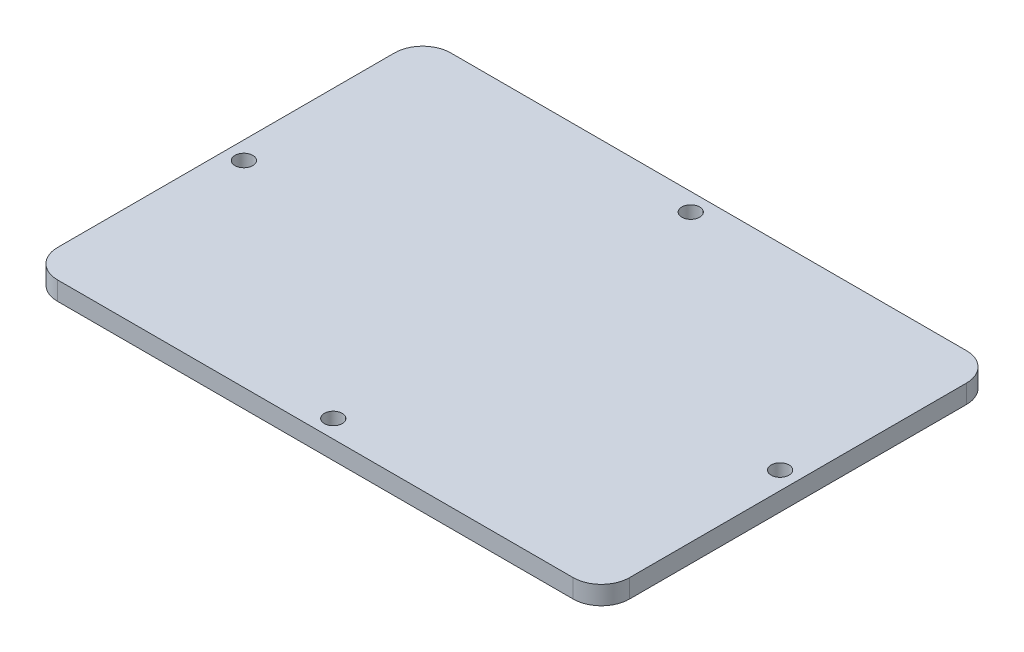
SolidWorks part; units mm, degrees
ref_plane "Front Plane" through (0, 0, 0) normal (0, 0, 1) x (1, 0, 0)
ref_plane "Top Plane" through (0, 0, 0) normal (0, 1, 0) x (1, 0, 0)
ref_plane "Right Plane" through (0, 0, 0) normal (1, 0, 0) x (0, 0, -1)
sketch "Sketch1" plane through (0, 0, 0) normal (0, 1, 0) x (1, 0, 0)
  line L1 (-50.8, -34.925) -> (50.8, -34.925)
  line L2 (-50.8, -34.925) -> (-50.8, 34.925)
  line L3 (-50.8, 34.925) -> (50.8, 34.925)
  line L4 (50.8, -34.925) -> (50.8, 34.925)
  line L5 (-50.8, -34.925) -> (50.8, 34.925) construction
  line L6 (-50.8, 34.925) -> (50.8, -34.925) construction
  point P0 (0, 0)
  point P6 (0, 0)
  point P7 (0, 0)
  dimension "D1" = 101.6
  dimension "D2" = 69.85
extrude "Boss-Extrude1" add sketch "Sketch1" along normal blind 3.302
sketch "Sketch4" plane through (0, 0, 0) normal (0, -1, 0) x (-1, 0, 0)
  circle A0 centre (0, 31.75) radius 1.5875
  circle A1 centre (-47.625, 0) radius 1.5875
  circle A2 centre (0, -31.75) radius 1.5875
  circle A3 centre (47.625, 0) radius 1.5875
  circle A8 centre (-47.625, 0) radius 1.5875 construction
  circle A9 centre (0, 31.75) radius 1.5875 construction
  circle A10 centre (0, -31.75) radius 1.5875 construction
  circle A11 centre (47.625, 0) radius 1.5875 construction
  point P10 (-18.2601, 23.8572)
  point P11 (25.4897, -1.9738)
  point P12 (0, -1.9738)
  point P13 (-18.2601, -4.7664)
extrude "Cut-Extrude1" cut sketch "Sketch4" against normal through all
fillet "Fillet1" radius 5 4 edges at (50.8, 1.651, -34.925) (50.8, 1.651, 34.925) (-50.8, 1.651, 34.925) (-50.8, 1.651, -34.925)
